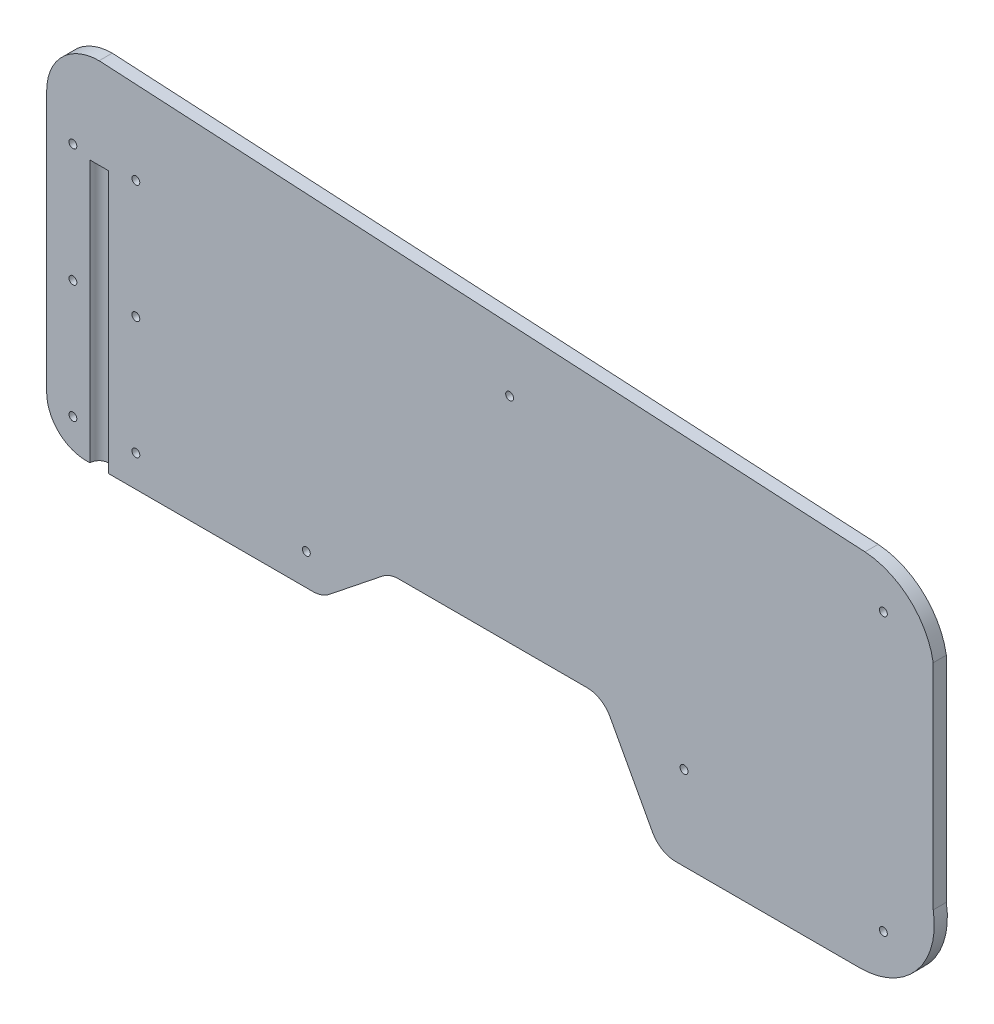
SolidWorks part; units mm, degrees
other "Folder spoin"
material "ABS PC"
ref_plane "Płaszczyzna przednia" through (0, 0, 0) normal (0, 0, 1) x (1, 0, 0)
ref_plane "Płaszczyzna górna" through (0, 0, 0) normal (0, 1, 0) x (1, 0, 0)
ref_plane "Płaszczyzna prawa" through (0, 0, 0) normal (1, 0, 0) x (0, 0, -1)
sketch "outer-wire" plane through (0, 0, 0) normal (0, 0, 1) x (1, 0, 0)
  line L0 (-24, -24.5302) -> (62.5, -24.5302)
  line L3 (-39, -9.5302) -> (-39, 90)
  line L4 (95.2361, -4) -> (167, -4)
  line L6 (176, -9.6411) -> (192, -39.2805)
  line L7 (68.7361, -22.3476) -> (89, -6.1826)
  line L10 (271, -44.5302) -> (200.7997, -44.5302)
  line L12 (299, -11.3778) -> (299, 70.2365)
  line L14 (-19, 110) -> (273, 93.8273)
  arc A0 (-39, -9.5302) -> (-24, -24.5302) centre (-24, -9.5302) ccw
  arc A1 (-19, 110) -> (-39, 90) centre (-19, 90) ccw
  arc A2 (62.5, -24.5302) -> (68.7361, -22.3476) centre (62.5, -14.5302) ccw
  arc A3 (89, -6.1826) -> (95.2361, -4) centre (95.2361, -14) cw
  arc A4 (271, -44.5302) -> (299, -11.3778) centre (271, -16.1298) ccw
  arc A5 (299, 70.2365) -> (273, 93.8273) centre (271, 65.5) ccw
  arc A6 (200.7997, -44.5302) -> (192, -39.2805) centre (200.7997, -34.5302) cw
  arc A7 (176, -9.6411) -> (167, -4) centre (167, -14) ccw
  point P14 (66, -24.5302)
  dimension "D2" = 20
  dimension "D1" = 15
  dimension "D7" = 66
  dimension "D8" = 89
  dimension "D10" = 167
  dimension "D17" = 271
  dimension "D18" = 273
  dimension "D20" = 39
  dimension "D21" = 110
  dimension "D4" = 28.4004
  dimension "D6" = 62.5
  dimension "D9" = 167
  dimension "D12" = 192
  dimension "D11" = 176
  dimension "D3" = 10
  dimension "D5" = 28.3978
  dimension "D13" = 65.5
  dimension "D14" = 4
  dimension "D15" = 71.7639
  dimension "D16" = 271
  dimension "D19" = 299
extrude "Dodanie-wyciągnięcie1" add sketch "outer-wire" along normal blind 5 contours L0 A2 L7 A3 L4 A7 L6 A6 L10 A4 L12 A5 L14 A1 L3 A0
ref_plane "Płaszczyzna6" through (0, -24.5302, 0) normal (0, -1, 0) x (-1, 0, 0)
sketch "Szkic1" plane through (0, -24.5302, 0) normal (0, -1, 0) x (-1, 0, 0)
  line L0 (24, 0) -> (-62.5, 0) construction
  line L1 (24, -5) -> (24, 0) construction
  circle A0 centre (19, 0) radius 3.5
  dimension "D1" = 7
  dimension "D2" = 5
extrude "Wytnij-wyciągnięcie1" cut sketch "Szkic1" against normal blind 100
ref_plane "Płaszczyzna12" through (0, 0, 5) normal (0, 0, 1) x (1, 0, 0)
sketch "Szkic3" plane through (0, 0, 5) normal (0, 0, 1) x (1, 0, 0)
  circle A0 centre (280, -28) radius 1.5
  circle A1 centre (280, 77.5) radius 1.5
  circle A2 centre (-5, 77.5) radius 1.5
  circle A3 centre (-29, 77.5) radius 1.5
  circle A4 centre (-29, -12.5) radius 1.5
  circle A5 centre (-29, 32.5) radius 1.5
  circle A6 centre (-5, 32.5) radius 1.5
  circle A7 centre (-5, -12.5) radius 1.5
  circle A8 centre (60, -12.5) radius 1.5
  circle A9 centre (204, -12.5) radius 1.5
  circle A10 centre (137.5, 77.5) radius 1.5
  dimension "D1" = 3
  dimension "D6" = 45
  dimension "D2" = 12.5
  dimension "D3" = 24
  dimension "D4" = 45
  dimension "D5" = 45
  dimension "D7" = 5
  dimension "D8" = 60
  dimension "D10" = 204
  dimension "D11" = 280
  dimension "D12" = 28
  dimension "D13" = 142.5
extrude "Wytnij-wyciągnięcie3" cut sketch "Szkic3" along direction (0, 0, 1) on the side against the normal blind 5 contours A4 | A5 | A3 | A2 | A6 | A7 | A8 | A10 | A9 | A0 | A1
ref_plane "Płaszczyzna13" through (0, 0, 5) normal (0, 0, 1) x (1, 0, 0)
sketch "Szkic5" plane through (0, 0, 5) normal (0, 0, 1) x (1, 0, 0)
  circle A0 centre (-29, -12.5) radius 3
  circle A1 centre (-29, 32.5) radius 3
  circle A2 centre (-29, 77.5) radius 3
  circle A3 centre (-5, 77.5) radius 3
  circle A4 centre (-5, 32.5) radius 3
  circle A5 centre (-5, -12.5) radius 3
  circle A6 centre (60, -12.5) radius 3
  circle A7 centre (137.5, 77.5) radius 3
  circle A8 centre (204, -12.5) radius 3
  circle A9 centre (280, -28) radius 3
  circle A10 centre (280, 77.5) radius 3
  dimension "D1" = 6
  dimension "D2" = 24
  dimension "D3" = 45
  dimension "D4" = 45
  dimension "D5" = 65
  dimension "D6" = 142.5
  dimension "D7" = 105.5
  dimension "D8" = 144
  dimension "D9" = 76
  dimension "D10" = 15.5
extrude "Wytnij-wyciągnięcie4" cut sketch "Szkic5" against normal blind 2.4 contours A0
mirror "Lustro4" about plane through (0, 0, 5) normal (0, 0, 1) of bodies 110
delete or keep bodies "Obiekt-Usuń/zachowaj 6" type delete bodies bodies 110
